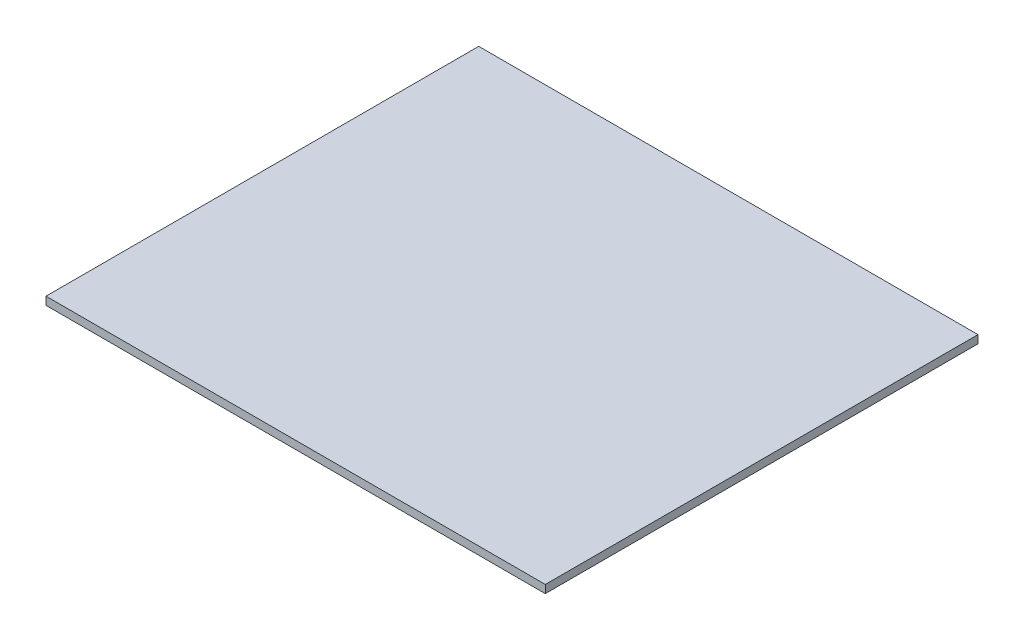
SolidWorks part; units mm, degrees
ref_plane "Front Plane" through (0, 0, 0) normal (0, 0, 1) x (1, 0, 0)
ref_plane "Top Plane" through (0, 0, 0) normal (0, 1, 0) x (1, 0, 0)
ref_plane "Right Plane" through (0, 0, 0) normal (1, 0, 0) x (0, 0, -1)
sketch "Sketch1" plane through (0, 0, 0) normal (0, 1, 0) x (1, 0, 0)
  line L1 (-37.5, -32.5) -> (37.5, -32.5)
  line L2 (-37.5, -32.5) -> (-37.5, 32.5)
  line L3 (-37.5, 32.5) -> (37.5, 32.5)
  line L4 (37.5, -32.5) -> (37.5, 32.5)
  line L5 (-37.5, -32.5) -> (37.5, 32.5) construction
  line L6 (-37.5, 32.5) -> (37.5, -32.5) construction
  point P0 (0, 0)
  dimension "D1" = 65
  dimension "D2" = 75
extrude "Boss-Extrude1" add sketch "Sketch1" along normal blind 1.2
